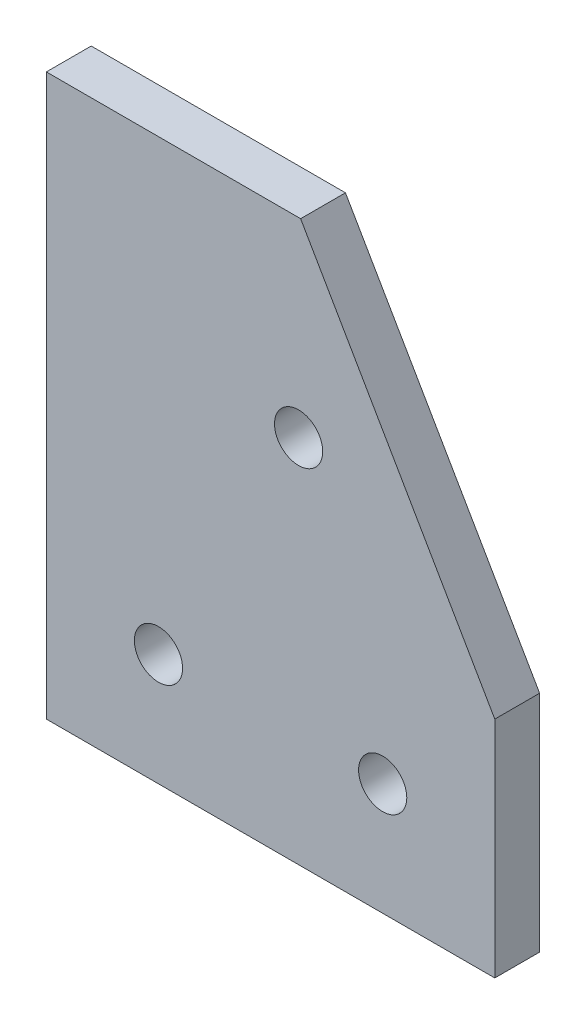
SolidWorks part; units mm, degrees
ref_plane "Front Plane" through (0, 0, 0) normal (0, 0, 1) x (1, 0, 0)
ref_plane "Top Plane" through (0, 0, 0) normal (0, 1, 0) x (1, 0, 0)
ref_plane "Right Plane" through (0, 0, 0) normal (1, 0, 0) x (0, 0, -1)
sketch "Sketch1" plane through (0, 0, 0) normal (0, 0, 1) x (1, 0, 0)
  line L1 (-20, 25) -> (20, 25)
  line L2 (-20, 25) -> (-20, -25)
  line L3 (-20, -25) -> (20, -25)
  line L4 (20, 25) -> (20, -25)
  line L5 (-20, 25) -> (20, -25) construction
  line L6 (-20, -25) -> (20, 25) construction
  point P0 (0, 0)
  dimension "D1" = 50
  dimension "D2" = 40
extrude "Boss-Extrude1" add sketch "Sketch1" along normal blind 4
sketch "Sketch3" plane through (0, 0, 4) normal (0, 0, 1) x (1, 0, 0)
  line L1 (20, -25) -> (20, 25) construction
  line L2 (20, 25) -> (2.68, 25) construction
  line L3 (20, 25) -> (-20, 25) construction
  line L4 (2.68, 25) -> (20, -5)
  line L5 (20, -5) -> (20, 25)
  line L6 (20, 25) -> (2.68, 25)
extrude "Cut-Extrude2" cut sketch "Sketch3" against normal through all
sketch "Sketch4" plane through (0, 0, 4) normal (0, 0, 1) x (1, 0, 0)
  line L0 (20, -5) -> (10, -5) construction
  line L2 (2.68, 25) -> (-7.32, 25) construction
  line L3 (2.68, 25) -> (-20, 25) construction
  line L5 (10, -5) -> (2.5002, 7.9905) construction
  circle A0 centre (2.5002, 7.9905) radius 2.15
  dimension "D1" = 10
  dimension "D2" = 10
  dimension "D3" = 34.6408
  dimension "D4" = 15
extrude "Cut-Extrude3" cut sketch "Sketch4" against normal through all
sketch "Sketch5" plane through (0, 0, 4) normal (0, 0, 1) x (1, 0, 0)
  line L0 (-20, -15) -> (-10, -15) construction
  line L3 (-20, 25) -> (-20, -25) construction
  line L5 (-10, -15) -> (-10, -25) construction
  line L6 (-20, -25) -> (20, -25) construction
  circle A1 centre (-10, -15) radius 2.15
  dimension "D1" = 10
  dimension "D2" = 10
extrude "Cut-Extrude4" cut sketch "Sketch5" against normal through all
sketch "Sketch8" plane through (0, 0, 4) normal (0, 0, 1) x (1, 0, 0)
  line L0 (20, -15) -> (10, -15) construction
  line L1 (20, -25) -> (20, -5) construction
  line L2 (-20, -25) -> (20, -25) construction
  line L3 (10, -15) -> (10, -25) construction
  circle A0 centre (10, -15) radius 2.15
  dimension "D1" = 10
  dimension "D2" = 10
extrude "Cut-Extrude5" cut sketch "Sketch8" against normal through all
